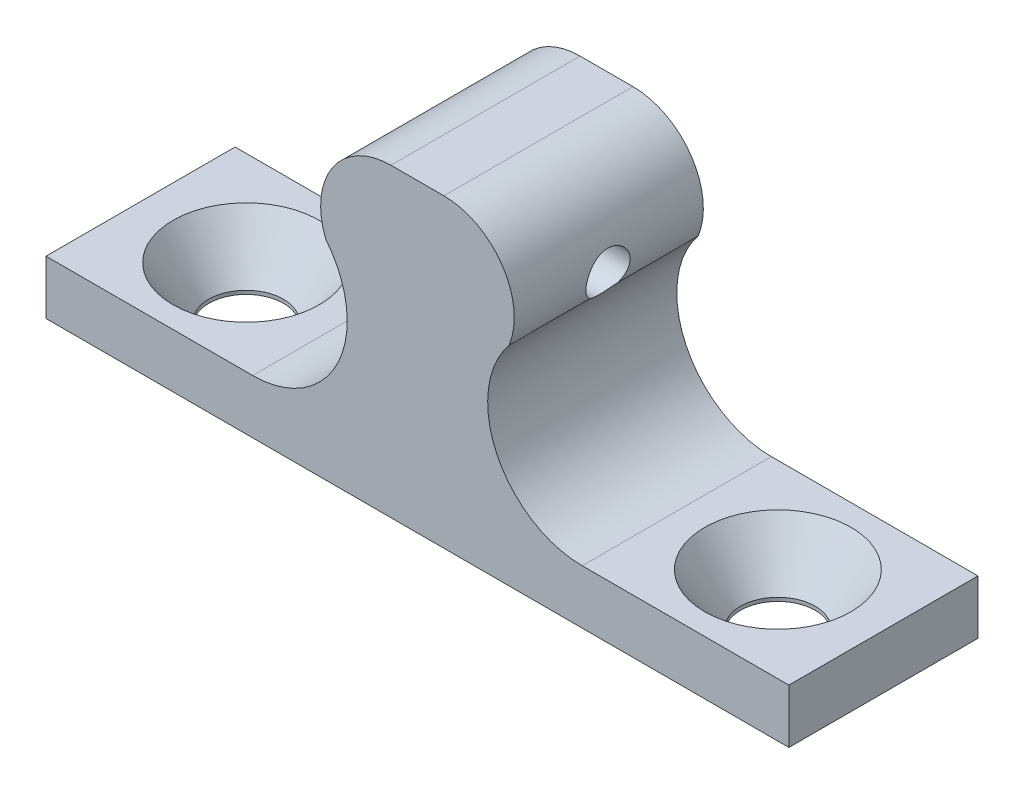
SolidWorks part; units mm, degrees
ref_plane "Front Plane" through (0, 0, 0) normal (0, 0, 1) x (1, 0, 0)
ref_plane "Top Plane" through (0, 0, 0) normal (0, 1, 0) x (1, 0, 0)
ref_plane "Right Plane" through (0, 0, 0) normal (1, 0, 0) x (0, 0, -1)
ref_plane "Plane1" through (0, 0, 21.5138) normal (0, 0, 1) x (1, 0, 0)
sketch "Sketch1" plane through (0, 0, 21.5138) normal (0, 0, 1) x (1, 0, 0)
  line L0 (9.7663, 28.448) -> (-1.8923, 28.448)
  line L1 (-1.8923, 28.448) -> (-1.8923, 25.4)
  line L2 (-1.8923, 25.4) -> (40.0177, 25.4)
  line L3 (40.0177, 25.4) -> (40.0177, 28.448)
  line L4 (40.0177, 28.448) -> (28.3591, 28.448)
  line L5 (20.5549, 42.6212) -> (17.5704, 42.6212)
  arc A0 (28.3591, 28.448) -> (24.2337, 37.1632) centre (28.3591, 33.782) cw
  arc A1 (24.2337, 37.1632) -> (20.5549, 42.6212) centre (20.5549, 38.6525) ccw
  arc A2 (17.5704, 42.6212) -> (13.8917, 37.1632) centre (17.5704, 38.6525) ccw
  arc A3 (13.8917, 37.1632) -> (9.7663, 28.448) centre (9.7663, 33.782) cw
extrude "Boss-Extrude1" add sketch "Sketch1" against normal blind 10.668
hole_wizard "CSK for #6 Flat Head Machine Screw (100)1" positions "Sketch3" profile "Sketch2" countersink size "#6" standard "ANSI Inch"
sketch "Sketch3" plane through (0, 28.448, 0) normal (0, 1, 0) x (1, 0, 0)
  point P0 (34.0614, -16.1798)
  point P1 (4.064, -16.1798)
sketch "Sketch2" plane through (34.0614, 28.448, 16.1798) normal (1, 0, 0) x (0, 0, 1)
  line L0 (0, 0) -> (0, 3.048)
  line L1 (0, 3.048) -> (2.1082, 3.048)
  line L2 (2.1082, 3.048) -> (2.1082, 2.8448)
  line L3 (2.1082, 2.8448) -> (4.1275, 0)
  line L5 (4.1275, 0) -> (0, 0)
  line L6 (-2.1082, 2.8448) -> (-4.1275, 0) construction
  line L11 (0, -6.35) -> (0, 107.95) construction
  dimension "Thru Hole Dia." = 4.2164
  dimension "Thru Hole Depth" = 3.048
  dimension "Near C'Sink Dia." = 8.255
  dimension "Near C'Sink Angle" = 70.736
sketch "Sketch4" plane through (0, 0, 0) normal (1, 0, 0) x (0, 0, -1)
  line L0 (-16.1798, 42.6212) -> (-16.1798, 25.0036) construction
  line L1 (-10.8458, 42.6212) -> (-21.5138, 42.6212) construction
  circle A0 centre (-16.1798, 38.109) radius 1.2383
extrude "Cut-Extrude1" cut sketch "Sketch4" along normal blind 2540
